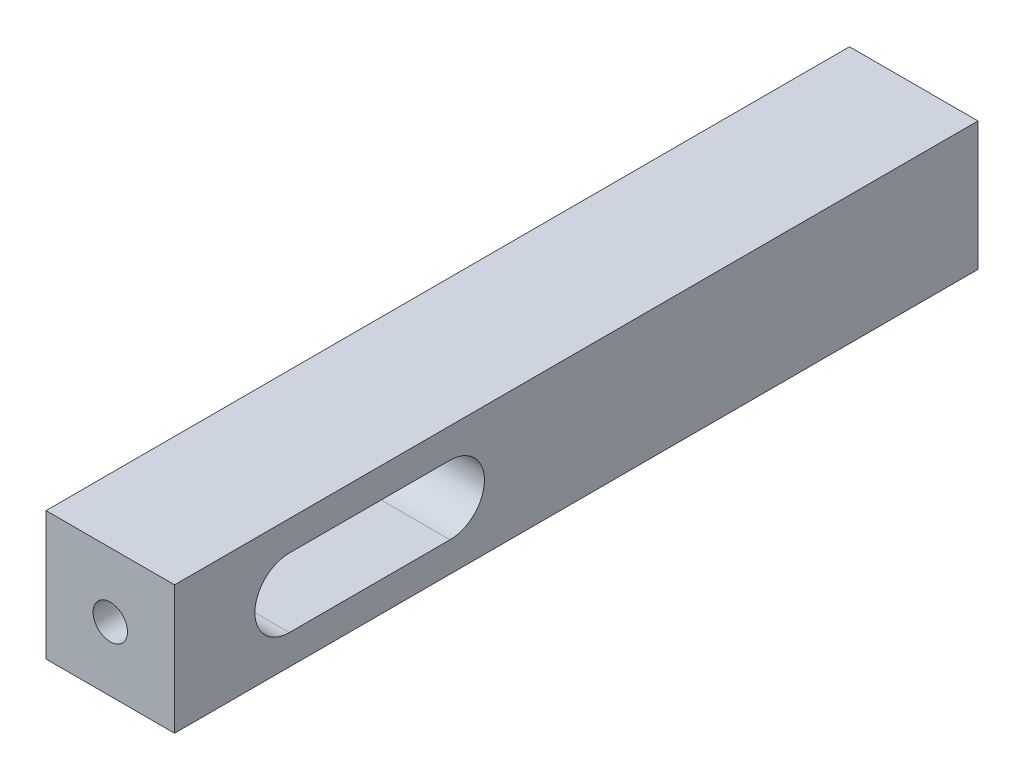
SolidWorks part; units mm, degrees
ref_plane "Front Plane" through (0, 0, 0) normal (0, 0, 1) x (1, 0, 0)
ref_plane "Top Plane" through (0, 0, 0) normal (0, 1, 0) x (1, 0, 0)
ref_plane "Right Plane" through (0, 0, 0) normal (1, 0, 0) x (0, 0, -1)
sketch "Sketch1" plane through (0, 0, 0) normal (0, 0, 1) x (1, 0, 0)
  line L1 (-2.8, 2.8) -> (2.8, 2.8)
  line L2 (-2.8, 2.8) -> (-2.8, -2.8)
  line L3 (-2.8, -2.8) -> (2.8, -2.8)
  line L4 (2.8, 2.8) -> (2.8, -2.8)
  line L5 (-2.8, 2.8) -> (2.8, -2.8) construction
  line L6 (-2.8, -2.8) -> (2.8, 2.8) construction
  circle A0 centre (0, 0) radius 0.75
  point P0 (0, 0)
  dimension "D2" = 1.5
  dimension "D1" = 5.6
extrude "Boss-Extrude1" add sketch "Sketch1" along normal blind 35
sketch "Sketch2" plane through (-2.8, 0, 0) normal (-1, 0, 0) x (0, 0, 1)
  line L0 (0, 0) -> (35, 0) construction
  line L1 (35, 2.8) -> (35, -2.8) construction
  line L2 (23, 0) -> (30, 0) construction
  line L3 (23, 1.5) -> (30, 1.5)
  line L4 (23, -1.5) -> (30, -1.5)
  arc A0 (23, 1.5) -> (23, -1.5) centre (23, 0) ccw
  arc A1 (30, -1.5) -> (30, 1.5) centre (30, 0) ccw
  point P7 (26.5, 0)
  dimension "D1" = 1.5
  dimension "D2" = 7
  dimension "D3" = 5
extrude "Cut-Extrude1" cut sketch "Sketch2" against normal through all
